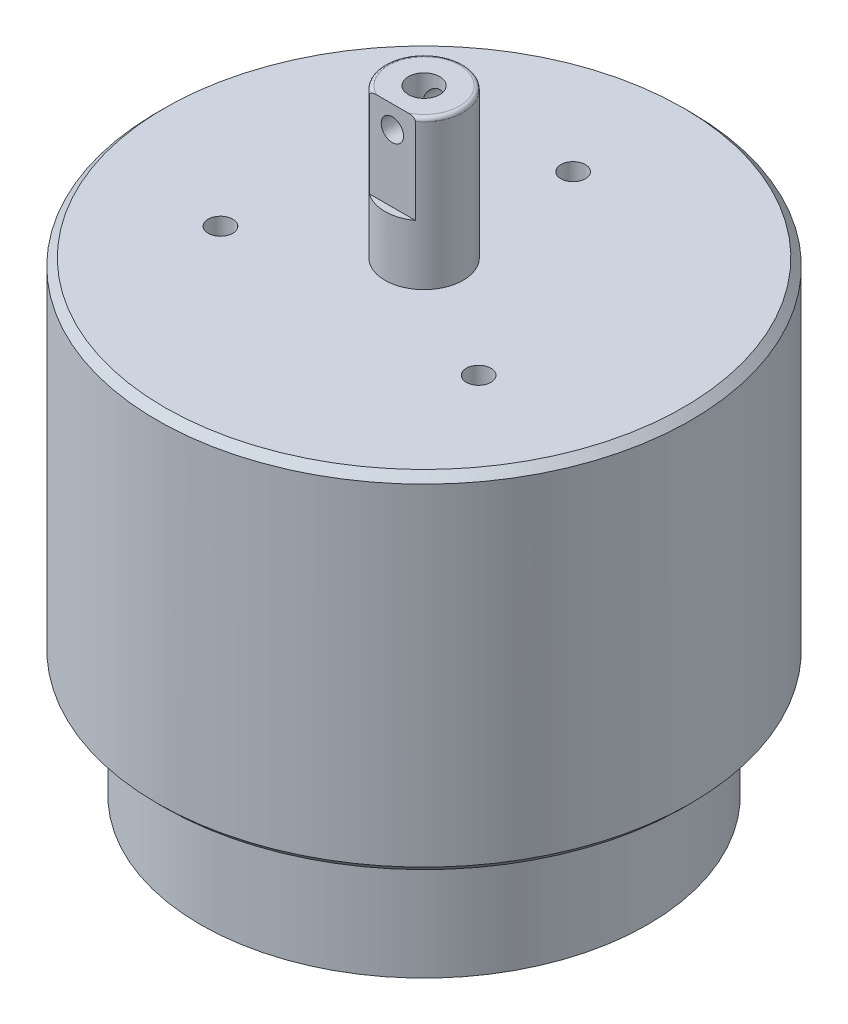
SolidWorks part; units mm, degrees
ref_plane "前视" through (0, 0, 0) normal (0, 0, 1) x (1, 0, 0)
ref_plane "上视" through (0, 0, 0) normal (0, 1, 0) x (1, 0, 0)
ref_plane "右视" through (0, 0, 0) normal (1, 0, 0) x (0, 0, -1)
sketch "草图1" plane through (0, 0, 0) normal (0, 1, 0) x (1, 0, 0)
  circle A0 centre (0, 0) radius 35.8
  dimension "D1" = 71.6
extrude "凸台-拉伸1" add sketch "草图1" along normal mid plane 46.5
sketch "草图2" plane through (0, 23.25, 0) normal (0, 1, 0) x (1, 0, 0)
  line L0 (-50.7598, 0) -> (65.2859, 0) construction
  line L1 (0, 61.6135) -> (0, -53.2896) construction
  point P5 (0, 20)
  point P6 (17.3205, -10)
  point P9 (-17.3205, -10)
  point P10 (0, 0)
  dimension "D1" = 20
  dimension "D2" = 3
hole_wizard "M4 螺纹孔1" positions "3D草图1" profile "草图3" tap size "M4" standard "Gb"
sketch3d "3D草图1"
  circle A0 centre (0, 0, 0) radius 30.6686
  circle A3 centre (-65.0821, 0, -92.5807) radius 17.4839
  point P0 (0, 23.25, -20)
  point P3 (-17.3205, 23.25, 10)
  point P6 (17.3205, 23.25, 10)
  point P12 (0, 20, 23.25)
  point P22 (-65.0821, 17.4839, -92.5807)
sketch "草图3" plane through (0, 23.25, -20) normal (1, 0, 0) x (0, 0, 1)
  line L0 (0, 0) -> (0, 12.4914)
  line L1 (0, 12.4914) -> (1.65, 11.5)
  line L2 (1.65, 11.5) -> (1.65, 0)
  line L5 (1.65, 0) -> (0, 0)
  line L10 (0, 12.4914) -> (-1.65, 11.5) construction
  line L11 (0, -6.35) -> (0, 107.95) construction
  dimension "螺纹孔钻头直径" = 3.3
  dimension "螺纹孔钻头深度" = 11.5
  dimension "导头角度" = 118
cosmetic thread "孔螺蚊线1" parameters "D1"=8, "D2"=4
cosmetic thread "孔螺蚊线2" parameters "D1"=8, "D2"=4
cosmetic thread "孔螺蚊线3" parameters "D1"=8, "D2"=4
sketch "草图4" plane through (0, 23.25, 0) normal (0, 1, 0) x (1, 0, 0)
  circle A0 centre (0, 0) radius 5.25
  dimension "D1" = 10.5
extrude "凸台-拉伸2" add sketch "草图4" along normal blind 20
fillet "圆角1" radius 0.5 1 edges at (0, 43.25, 5.25)
sketch "草图5" plane through (0, 43.25, 0) normal (0, 1, 0) x (1, 0, 0)
  line L0 (0, 61.6135) -> (0, -53.2896) construction
  line L1 (-4.814, -4.25) -> (4.814, -4.25)
  line L2 (-4.814, -4.25) -> (-4.814, -6.25)
  line L3 (-4.814, -6.25) -> (4.814, -6.25)
  line L4 (4.814, -4.25) -> (4.814, -6.25)
  line L5 (-4.814, -4.25) -> (4.814, -6.25) construction
  line L6 (-4.814, -6.25) -> (4.814, -4.25) construction
  circle A0 centre (0, 0) radius 5.25 construction
  point P0 (0, -5.25)
  dimension "D1" = 1
extrude "切除-拉伸1" cut sketch "草图5" against normal blind 12
hole_wizard "M5 螺纹孔1" positions "3D草图2" profile "草图6" tap size "M5" standard "Gb"
sketch3d "3D草图2"
  line L0 (0, 39.9163, 0) -> (0, 48.4175, 0) construction
  point P0 (0, 43.25, 0)
sketch "草图6" plane through (0, 43.25, 0) normal (1, 0, 0) x (0, 0, 1)
  line L0 (0, 0) -> (0, 15.2618)
  line L1 (0, 15.2618) -> (2.1, 14)
  line L2 (2.1, 14) -> (2.1, 0)
  line L5 (2.1, 0) -> (0, 0)
  line L10 (0, 15.2618) -> (-2.1, 14) construction
  line L11 (0, -6.35) -> (0, 107.95) construction
  dimension "螺纹孔钻头直径" = 4.2
  dimension "螺纹孔钻头深度" = 14
  dimension "导头角度" = 118
cosmetic thread "孔螺蚊线4" parameters "D1"=10, "D2"=5
chamfer "倒角1" distance 1 angle 45 1 edges at (0, 23.25, 35.8)
sketch "草图7" plane through (0, -23.25, 0) normal (0, -1, 0) x (1, 0, 0)
  circle A0 centre (0, 0) radius 30
  dimension "D1" = 60
extrude "凸台-拉伸3" add sketch "草图7" along normal blind 17
chamfer "倒角2" distance 1 angle 45 1 edges at (0, -23.25, 35.8)
chamfer "倒角3" distance 1 distance2 3 1 edges at (0, -40.25, -30)
sketch "草图8" plane through (0, 0, 4.25) normal (0, 0, 1) x (1, 0, 0)
  line L0 (2.1213, 43.25) -> (-2.1213, 43.25) construction
  circle A0 centre (0, 40.25) radius 1.5
  dimension "D1" = 3
  dimension "D2" = 3
extrude "切除-拉伸2" cut sketch "草图8" against normal through all
